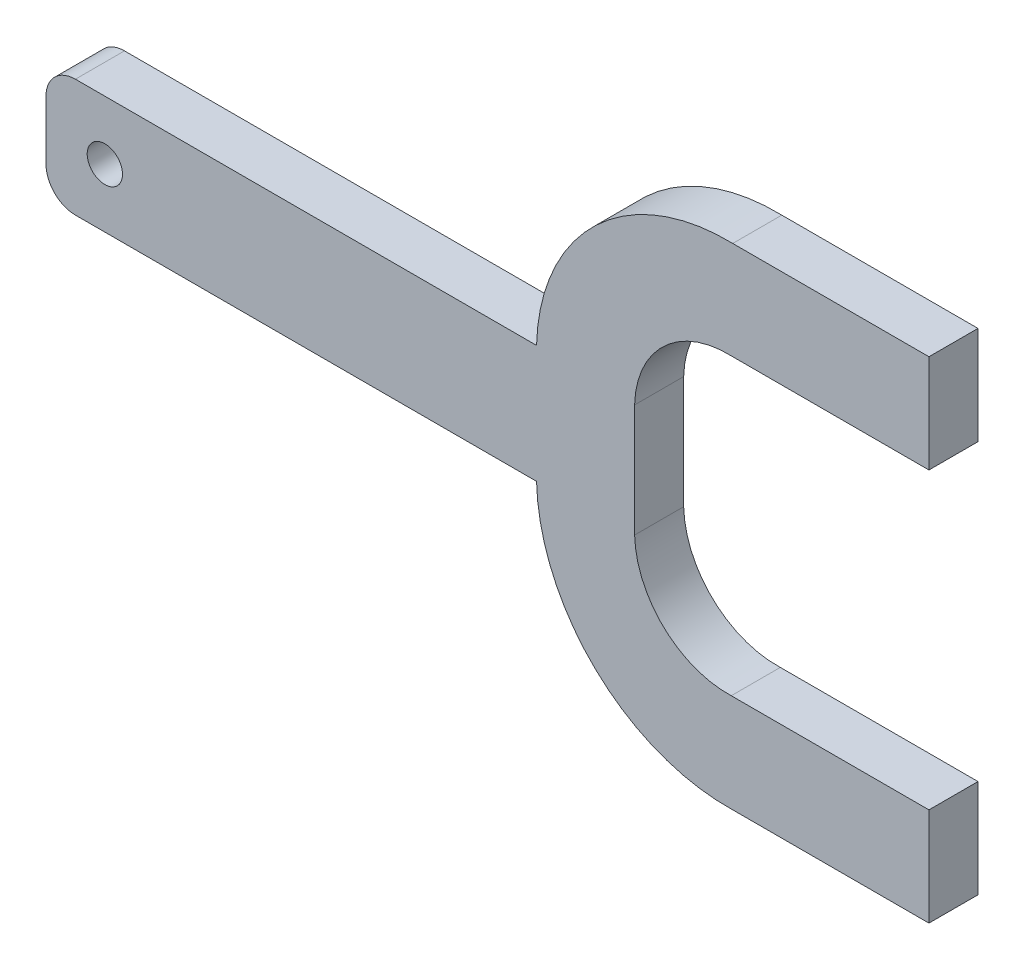
SolidWorks part; units mm, degrees
ref_plane "Front Plane" through (0, 0, 0) normal (0, 0, 1) x (1, 0, 0)
ref_plane "Top Plane" through (0, 0, 0) normal (0, 1, 0) x (1, 0, 0)
ref_plane "Right Plane" through (0, 0, 0) normal (1, 0, 0) x (0, 0, -1)
sketch "Sketch1" plane through (0, 0, 0) normal (0, 0, 1) x (1, 0, 0)
  line L0 (0, 6) -> (128.2333, 6) construction
  line L1 (3, 0) -> (50, 0)
  line L2 (0, 3) -> (0, 9)
  line L3 (3, 12) -> (50, 12)
  line L4 (50, 0) -> (50, 12)
  line L5 (50, 31) -> (90, 31) construction
  line L6 (50, 31) -> (50, -19) construction
  line L7 (50, -19) -> (90, -19) construction
  line L8 (90, 31) -> (90, -19) construction
  line L9 (90, 31) -> (70, 31)
  line L10 (90, -19) -> (70, -19)
  line L11 (90, 21) -> (69.849, 21)
  line L12 (90, -9) -> (69.849, -9)
  line L13 (59.9967, 11.7437) -> (59.9967, 0.2563)
  line L14 (90, 31) -> (90, 21)
  line L15 (90, -9) -> (90, -19)
  arc A0 (70, 31) -> (50, 12) centre (69.5, 11.5) ccw
  arc A1 (70, -19) -> (50, 0) centre (69.5, 0.5) cw
  arc A2 (69.849, 21) -> (59.9967, 11.7437) centre (69.5, 11.5) ccw
  arc A3 (69.849, -9) -> (59.9967, 0.2563) centre (69.5, 0.5) cw
  arc A4 (3, 0) -> (0, 3) centre (3, 3) cw
  arc A5 (0, 9) -> (3, 12) centre (3, 9) cw
  circle A6 centre (6, 6) radius 1.8
  point P11 (90, 6)
  point P26 (0, 0)
  point P29 (0, 12)
  dimension "D7" = 3
  dimension "D8" = 3.6
  dimension "D1" = 50
  dimension "D2" = 12
  dimension "D3" = 40
  dimension "D4" = 50
  dimension "D9" = 6
  dimension "D5" = 10
  dimension "D6" = 10
extrude "Boss-Extrude2" add sketch "Sketch1" along normal blind 5 contours A5 L2 A4 L1 L4 L3 A6 | L12 A3 L13 A2 L11 L14 L9 A0 L4 A1 L10 L15
